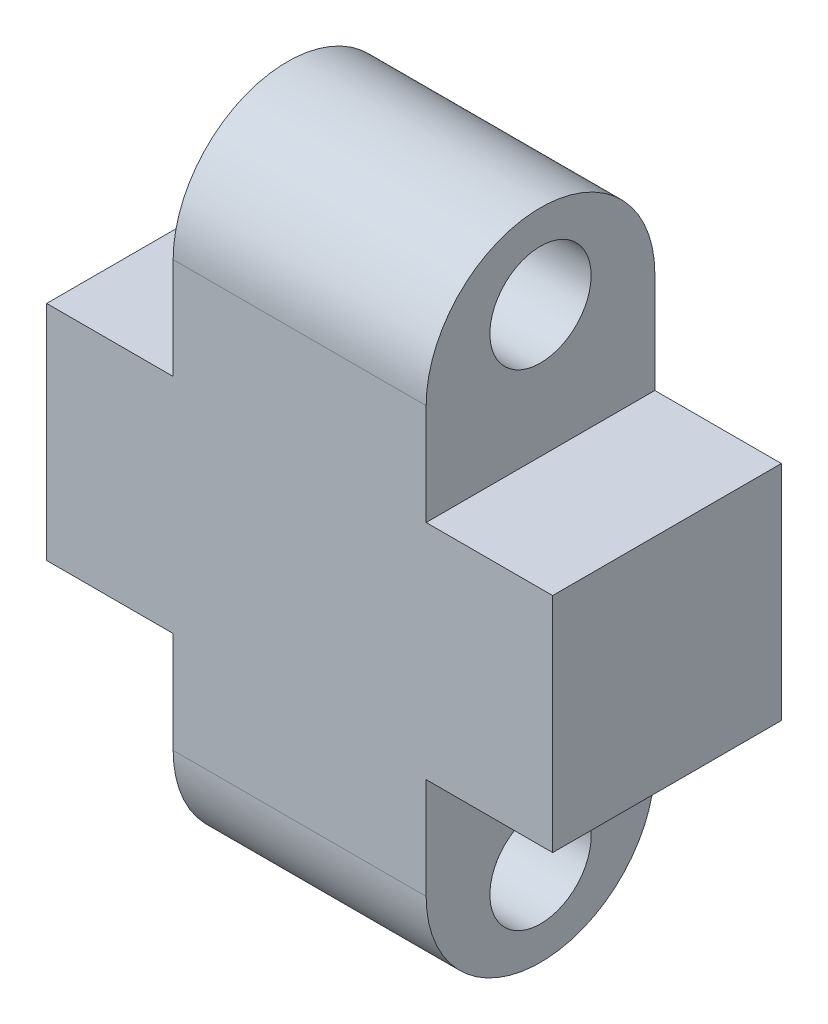
SolidWorks part; units mm, degrees
ref_plane "Front Plane" through (0, 0, 0) normal (0, 0, 1) x (1, 0, 0)
ref_plane "Top Plane" through (0, 0, 0) normal (0, 1, 0) x (1, 0, 0)
ref_plane "Right Plane" through (0, 0, 0) normal (1, 0, 0) x (0, 0, -1)
sketch "Sketch1" plane through (0, 0, 0) normal (0, 0, 1) x (1, 0, 0)
  line L1 (-25, 11) -> (25, 11)
  line L2 (-25, 11) -> (-25, -11)
  line L3 (-25, -11) -> (25, -11)
  line L4 (25, 11) -> (25, -11)
  line L5 (0, -11) -> (0, 11) construction
  line L6 (-25, 0) -> (25, 0) construction
  point P0 (0, 0)
  dimension "D1" = 50
  dimension "D2" = 22
extrude "Boss-Extrude1" add sketch "Sketch1" along normal blind 22.6
sketch "Sketch3" plane through (0, 0, 0) normal (1, 0, 0) x (0, 0, -1)
  line L0 (-22.6, 11) -> (-22.6, 21)
  line L1 (0, 21) -> (0, 11)
  line L2 (0, 11) -> (-22.6, 11)
  arc A0 (-22.6, 21) -> (0, 21) centre (-11.3, 21) cw
  circle A1 centre (-11.3, 24) radius 5
  point P9 (0, 0)
  dimension "D2" = 10
  dimension "D3" = 13
  dimension "D1" = 10
extrude "Boss-Extrude2" add sketch "Sketch3" along normal mid plane 25
mirror "Mirror1" about plane through (0, 0, 0) normal (0, 1, 0) of "Boss-Extrude2"
